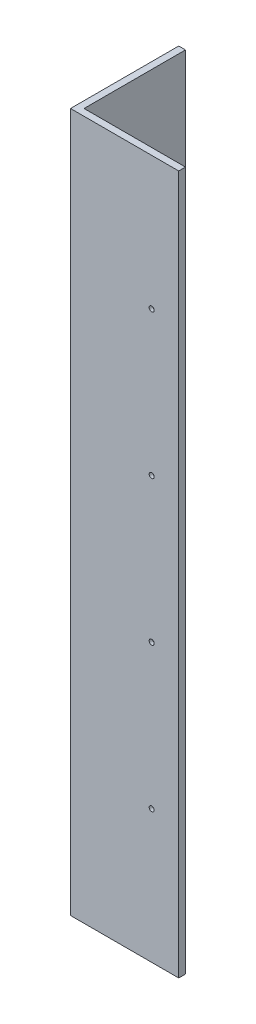
SolidWorks part; units mm, degrees
material "Custom Plastic"
ref_plane "Front Plane" through (0, 0, 0) normal (0, 0, 1) x (1, 0, 0)
ref_plane "Top Plane" through (0, 0, 0) normal (0, 1, 0) x (1, 0, 0)
ref_plane "Right Plane" through (0, 0, 0) normal (1, 0, 0) x (0, 0, -1)
sketch "Sketch2" plane through (0, 0, 0) normal (0, 0, 1) x (1, 0, 0)
  line L1 (-68.6643, 36.2418) -> (83.7357, 36.2418)
  line L2 (-68.6643, 36.2418) -> (-68.6643, -948.0082)
  line L3 (-68.6643, -948.0082) -> (83.7357, -948.0082)
  line L4 (83.7357, 36.2418) -> (83.7357, -948.0082)
extrude "Boss-Extrude1" add sketch "Sketch2" along normal blind 9.525
sketch "Sketch4" plane through (-68.6643, 0, 0) normal (-1, 0, 0) x (0, 0, 1)
  line L0 (0, -948.0082) -> (-142.875, -948.0082)
  line L1 (-142.875, -948.0082) -> (-142.875, 36.2418)
  line L2 (-142.875, 36.2418) -> (0, 36.2418)
  line L3 (0, 36.2418) -> (0, -948.0082)
extrude "Boss-Extrude2" add sketch "Sketch4" against normal blind 9.525
sketch "Sketch5" plane through (-68.6643, 0, 0) normal (-1, 0, 0) x (0, 0, 1)
  line L0 (-142.875, 36.2418) -> (-142.875, -948.0082) construction
  line L1 (9.525, 36.2418) -> (-142.875, 36.2418) construction
  circle A0 centre (-104.775, -151.0832) radius 3.5687
  circle A2 centre (-104.775, -354.2832) radius 3.5687
  circle A3 centre (-104.775, -557.4832) radius 3.5687
  circle A4 centre (-104.775, -760.6832) radius 3.5687
  dimension "D1" = 38.1
  dimension "D2" = 187.325
  dimension "D5" = 38.1
  dimension "D6" = 38.1
  dimension "D7" = 38.1
  dimension "D9" = 203.2
  dimension "D10" = 203.2
  dimension "D11" = 203.2
extrude "Cut-Extrude1" cut sketch "Sketch5" against normal blind 9.525
sketch "Sketch6" plane through (0, 0, 9.525) normal (0, 0, 1) x (1, 0, 0)
  line L0 (83.7357, -948.0082) -> (83.7357, 36.2418) construction
  line L1 (83.7357, 36.2418) -> (-68.6643, 36.2418) construction
  circle A0 centre (45.6357, -151.0832) radius 3.5687
  circle A1 centre (45.6357, -354.2832) radius 3.5687
  circle A2 centre (45.6357, -557.4832) radius 3.5687
  circle A3 centre (45.6357, -760.6832) radius 3.5687
  dimension "D1" = 38.1
  dimension "D2" = 187.325
  dimension "D3" = 38.1
  dimension "D4" = 38.1
  dimension "D5" = 38.1
  dimension "D8" = 203.2
  dimension "D9" = 203.2
  dimension "D10" = 203.2
extrude "Cut-Extrude2" cut sketch "Sketch6" against normal blind 9.525
hole_wizard "CSK for 1/4 Flat Head Machine Screw1" positions "3DSketch1" profile "Sketch7" countersink size "1/4" standard "ANSI Inch" end condition through all
sketch3d "3DSketch1"
  line L0 (-59.1393, -151.0832, -104.775) -> (-68.6643, -151.0832, -104.775) construction
  point P0 (-59.1393, -151.0832, -104.775)
sketch "Sketch7" plane through (-59.1393, -151.0832, -104.775) normal (0, 1, 0) x (0, 0, -1)
  line L0 (0, 0) -> (0, 9.525)
  line L1 (0, 9.525) -> (3.3782, 9.525)
  line L2 (3.3782, 9.525) -> (3.3782, 5.0449)
  line L3 (3.3782, 5.0449) -> (7.7637, 0)
  line L5 (7.7637, 0) -> (0, 0)
  line L6 (-3.3782, 5.0449) -> (-7.7637, 0) construction
  line L11 (0, -6.35) -> (0, 107.95) construction
  dimension "Thru Hole Dia." = 6.7564
  dimension "Thru Hole Depth" = 9.525
  dimension "Near C'Sink Dia." = 15.5274
  dimension "Near C'Sink Angle" = 82
hole_wizard "CSK for 1/4 Flat Head Machine Screw2" positions "3DSketch2" profile "Sketch8" countersink size "1/4" standard "ANSI Inch" end condition through all
sketch3d "3DSketch2"
  line L0 (-59.1393, -354.2832, -104.775) -> (-68.6643, -354.2832, -104.775) construction
  point P0 (-59.1393, -354.2832, -104.775)
sketch "Sketch8" plane through (-59.1393, -354.2832, -104.775) normal (0, 1, 0) x (0, 0, -1)
  line L0 (0, 0) -> (0, 9.525)
  line L1 (0, 9.525) -> (3.3782, 9.525)
  line L2 (3.3782, 9.525) -> (3.3782, 5.0449)
  line L3 (3.3782, 5.0449) -> (7.7637, 0)
  line L5 (7.7637, 0) -> (0, 0)
  line L6 (-3.3782, 5.0449) -> (-7.7637, 0) construction
  line L11 (0, -6.35) -> (0, 107.95) construction
  dimension "Thru Hole Dia." = 6.7564
  dimension "Thru Hole Depth" = 9.525
  dimension "Near C'Sink Dia." = 15.5274
  dimension "Near C'Sink Angle" = 82
hole_wizard "CSK for 1/4 Flat Head Machine Screw (100)4" positions "3DSketch4" profile "Sketch10" countersink size "1/4" standard "ANSI Inch" end condition through all
sketch3d "3DSketch4"
  line L0 (-59.1393, -760.6832, -104.775) -> (-68.6643, -760.6832, -104.775) construction
  point P0 (-59.1393, -760.6832, -104.775)
sketch "Sketch10" plane through (-59.1393, -760.6832, -104.775) normal (0, 1, 0) x (0, 0, -1)
  line L0 (0, 0) -> (0, 9.525)
  line L1 (0, 9.525) -> (3.3782, 9.525)
  line L2 (3.3782, 9.525) -> (3.3782, 4.0922)
  line L3 (3.3782, 4.0922) -> (8.2551, 0)
  line L5 (8.2551, 0) -> (0, 0)
  line L6 (-3.3782, 4.0922) -> (-8.2551, 0) construction
  line L11 (0, -6.35) -> (0, 107.95) construction
  dimension "Thru Hole Dia." = 6.7564
  dimension "Thru Hole Depth" = 9.525
  dimension "Near C'Sink Dia." = 16.5103
  dimension "Near C'Sink Angle" = 100
hole_wizard "CSK for 1/4 Flat Head Machine Screw5" positions "3DSketch5" profile "Sketch11" countersink size "1/4" standard "ANSI Inch" end condition through all
sketch3d "3DSketch5"
  line L0 (45.6357, -151.0832, 0) -> (45.6357, -151.0832, 9.525) construction
  point P0 (45.6357, -151.0832, 0)
sketch "Sketch11" plane through (45.6357, -151.0832, 0) normal (1, 0, 0) x (0, 1, 0)
  line L0 (0, 0) -> (0, 9.525)
  line L1 (0, 9.525) -> (3.3782, 9.525)
  line L2 (3.3782, 9.525) -> (3.3782, 5.0449)
  line L3 (3.3782, 5.0449) -> (7.7637, 0)
  line L5 (7.7637, 0) -> (0, 0)
  line L6 (-3.3782, 5.0449) -> (-7.7637, 0) construction
  line L11 (0, -6.35) -> (0, 107.95) construction
  dimension "Thru Hole Dia." = 6.7564
  dimension "Thru Hole Depth" = 9.525
  dimension "Near C'Sink Dia." = 15.5274
  dimension "Near C'Sink Angle" = 82
hole_wizard "CSK for 1/4 Flat Head Machine Screw6" positions "3DSketch6" profile "Sketch12" countersink size "1/4" standard "ANSI Inch" end condition through all
sketch3d "3DSketch6"
  line L0 (45.6357, -354.2832, 0) -> (45.6357, -354.2832, 9.525) construction
  point P0 (45.6357, -354.2832, 0)
sketch "Sketch12" plane through (45.6357, -354.2832, 0) normal (1, 0, 0) x (0, 1, 0)
  line L0 (0, 0) -> (0, 9.525)
  line L1 (0, 9.525) -> (3.3782, 9.525)
  line L2 (3.3782, 9.525) -> (3.3782, 5.0449)
  line L3 (3.3782, 5.0449) -> (7.7637, 0)
  line L5 (7.7637, 0) -> (0, 0)
  line L6 (-3.3782, 5.0449) -> (-7.7637, 0) construction
  line L11 (0, -6.35) -> (0, 107.95) construction
  dimension "Thru Hole Dia." = 6.7564
  dimension "Thru Hole Depth" = 9.525
  dimension "Near C'Sink Dia." = 15.5274
  dimension "Near C'Sink Angle" = 82
hole_wizard "CSK for 1/4 Flat Head Machine Screw7" positions "3DSketch7" profile "Sketch13" countersink size "1/4" standard "ANSI Inch" end condition through all
sketch3d "3DSketch7"
  line L0 (45.6357, -557.4832, 0) -> (45.6357, -557.4832, 9.525) construction
  point P0 (45.6357, -557.4832, 0)
sketch "Sketch13" plane through (45.6357, -557.4832, 0) normal (1, 0, 0) x (0, 1, 0)
  line L0 (0, 0) -> (0, 9.525)
  line L1 (0, 9.525) -> (3.3782, 9.525)
  line L2 (3.3782, 9.525) -> (3.3782, 5.0449)
  line L3 (3.3782, 5.0449) -> (7.7637, 0)
  line L5 (7.7637, 0) -> (0, 0)
  line L6 (-3.3782, 5.0449) -> (-7.7637, 0) construction
  line L11 (0, -6.35) -> (0, 107.95) construction
  dimension "Thru Hole Dia." = 6.7564
  dimension "Thru Hole Depth" = 9.525
  dimension "Near C'Sink Dia." = 15.5274
  dimension "Near C'Sink Angle" = 82
hole_wizard "CSK for 1/4 Flat Head Machine Screw8" positions "3DSketch8" profile "Sketch14" countersink size "1/4" standard "ANSI Inch" end condition through all
sketch3d "3DSketch8"
  line L0 (45.6357, -760.6832, 0) -> (45.6357, -760.6832, 9.525) construction
  point P0 (45.6357, -760.6832, 0)
sketch "Sketch14" plane through (45.6357, -760.6832, 0) normal (1, 0, 0) x (0, 1, 0)
  line L0 (0, 0) -> (0, 9.525)
  line L1 (0, 9.525) -> (3.3782, 9.525)
  line L2 (3.3782, 9.525) -> (3.3782, 5.0449)
  line L3 (3.3782, 5.0449) -> (7.7637, 0)
  line L5 (7.7637, 0) -> (0, 0)
  line L6 (-3.3782, 5.0449) -> (-7.7637, 0) construction
  line L11 (0, -6.35) -> (0, 107.95) construction
  dimension "Thru Hole Dia." = 6.7564
  dimension "Thru Hole Depth" = 9.525
  dimension "Near C'Sink Dia." = 15.5274
  dimension "Near C'Sink Angle" = 82
hole_wizard "CSK for 1/4 Flat Head Machine Screw4" positions "3DSketch9" profile "Sketch15" countersink size "1/4" standard "ANSI Inch" end condition through all
sketch3d "3DSketch9"
  line L0 (-59.1393, -557.4832, -104.775) -> (-68.6643, -557.4832, -104.775) construction
  point P0 (-59.1393, -557.4832, -104.775)
sketch "Sketch15" plane through (-59.1393, -557.4832, -104.775) normal (0, 1, 0) x (0, 0, -1)
  line L0 (0, 0) -> (0, 9.525)
  line L1 (0, 9.525) -> (3.3782, 9.525)
  line L2 (3.3782, 9.525) -> (3.3782, 5.0449)
  line L3 (3.3782, 5.0449) -> (7.7637, 0)
  line L5 (7.7637, 0) -> (0, 0)
  line L6 (-3.3782, 5.0449) -> (-7.7637, 0) construction
  line L11 (0, -6.35) -> (0, 107.95) construction
  dimension "Thru Hole Dia." = 6.7564
  dimension "Thru Hole Depth" = 9.525
  dimension "Near C'Sink Dia." = 15.5274
  dimension "Near C'Sink Angle" = 82
